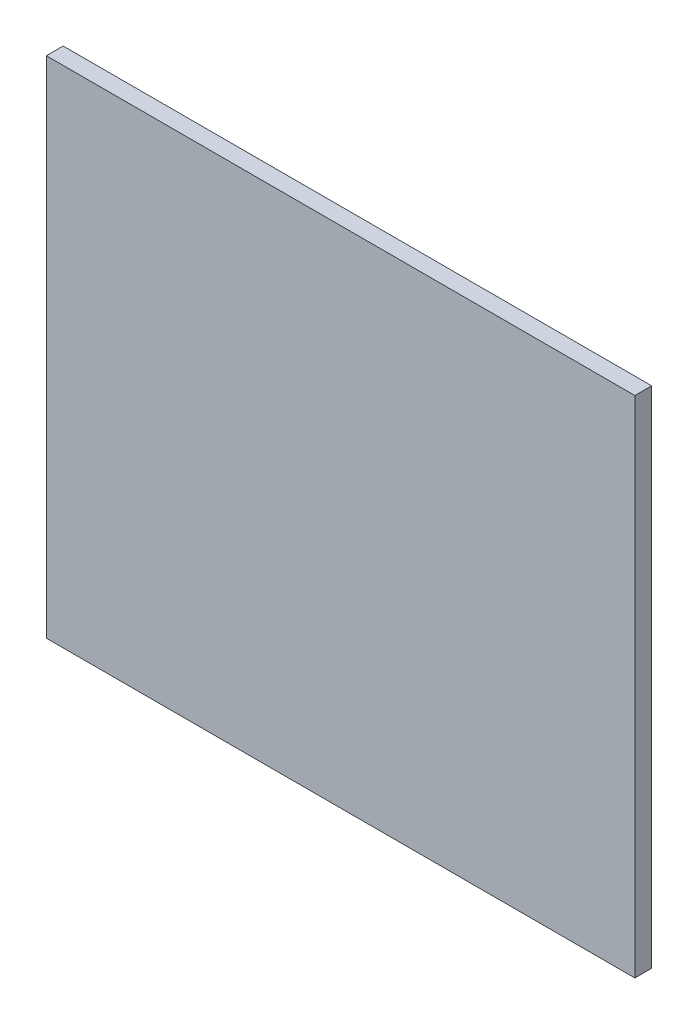
SolidWorks part; units mm, degrees
ref_plane "前视基准面" through (0, 0, 0) normal (0, 0, 1) x (1, 0, 0)
ref_plane "上视基准面" through (0, 0, 0) normal (0, 1, 0) x (1, 0, 0)
ref_plane "右视基准面" through (0, 0, 0) normal (1, 0, 0) x (0, 0, -1)
other "Configuration Table"
sketch "草图1" plane through (0, 0, 0) normal (0, 0, 1) x (1, 0, 0)
  line L1 (-350, -300) -> (350, -300)
  line L2 (-350, -300) -> (-350, 300)
  line L3 (-350, 300) -> (350, 300)
  line L4 (350, -300) -> (350, 300)
  line L5 (-350, -300) -> (350, 300) construction
  line L6 (-350, 300) -> (350, -300) construction
  point P0 (0, 0)
extrude "凸台-拉伸1" add sketch "草图1" along normal blind 20
